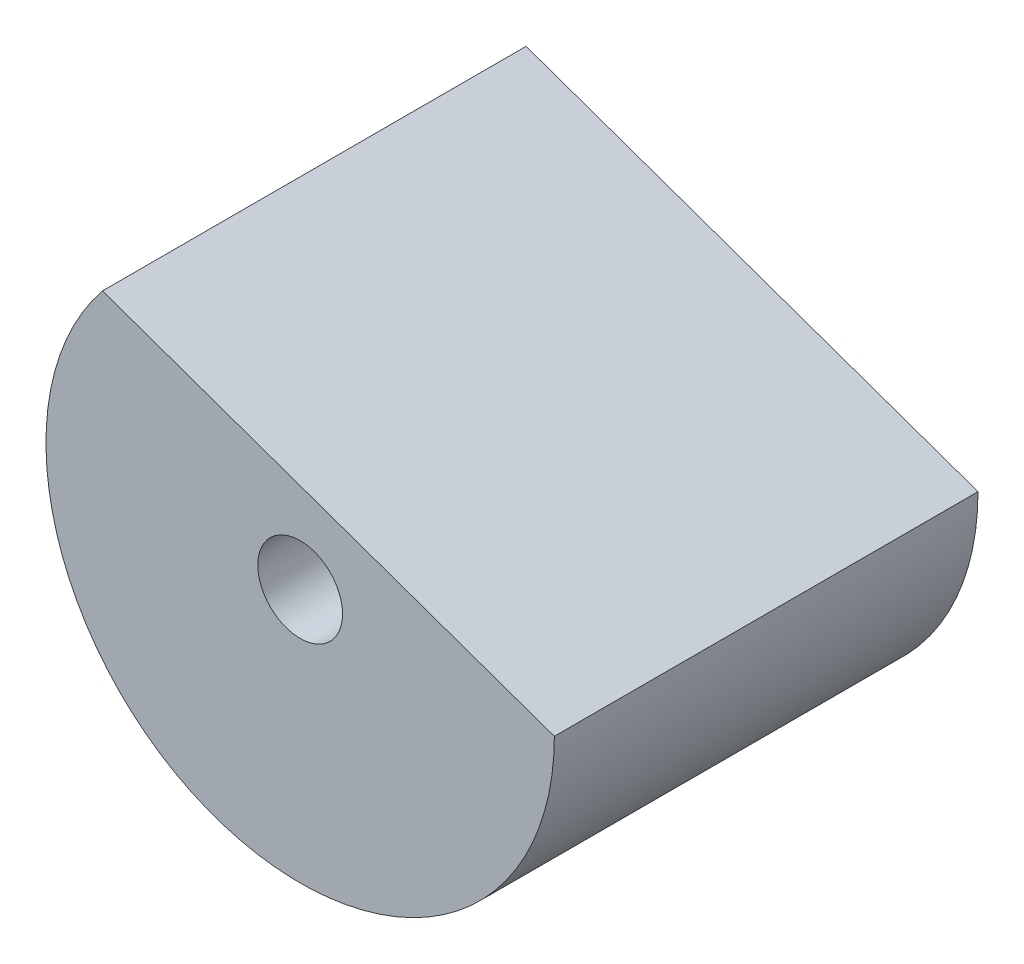
SolidWorks part; units mm, degrees
ref_plane "Piano frontale" through (0, 0, 0) normal (0, 0, 1) x (1, 0, 0)
ref_plane "Piano superiore" through (0, 0, 0) normal (0, 1, 0) x (1, 0, 0)
ref_plane "Piano destro" through (0, 0, 0) normal (1, 0, 0) x (0, 0, -1)
sketch "Schizzo1" plane through (0, 0, 0) normal (0, 0, 1) x (1, 0, 0)
  line L0 (3, 0) -> (-2.3333, 1.8856)
  circle A0 centre (0, 0) radius 0.5
  arc A1 (-2.3333, 1.8856) -> (3, 0) centre (0, 0) ccw
  point P6 (-2.2674, 1.9645)
  point P7 (-2.8073, 1.0579)
  point P8 (0, 0)
  dimension "D1" = 1
  dimension "D2" = 6
  dimension "D3" = 1
extrude "Estrusione-Estrusione1" add sketch "Schizzo1" along normal blind 5
